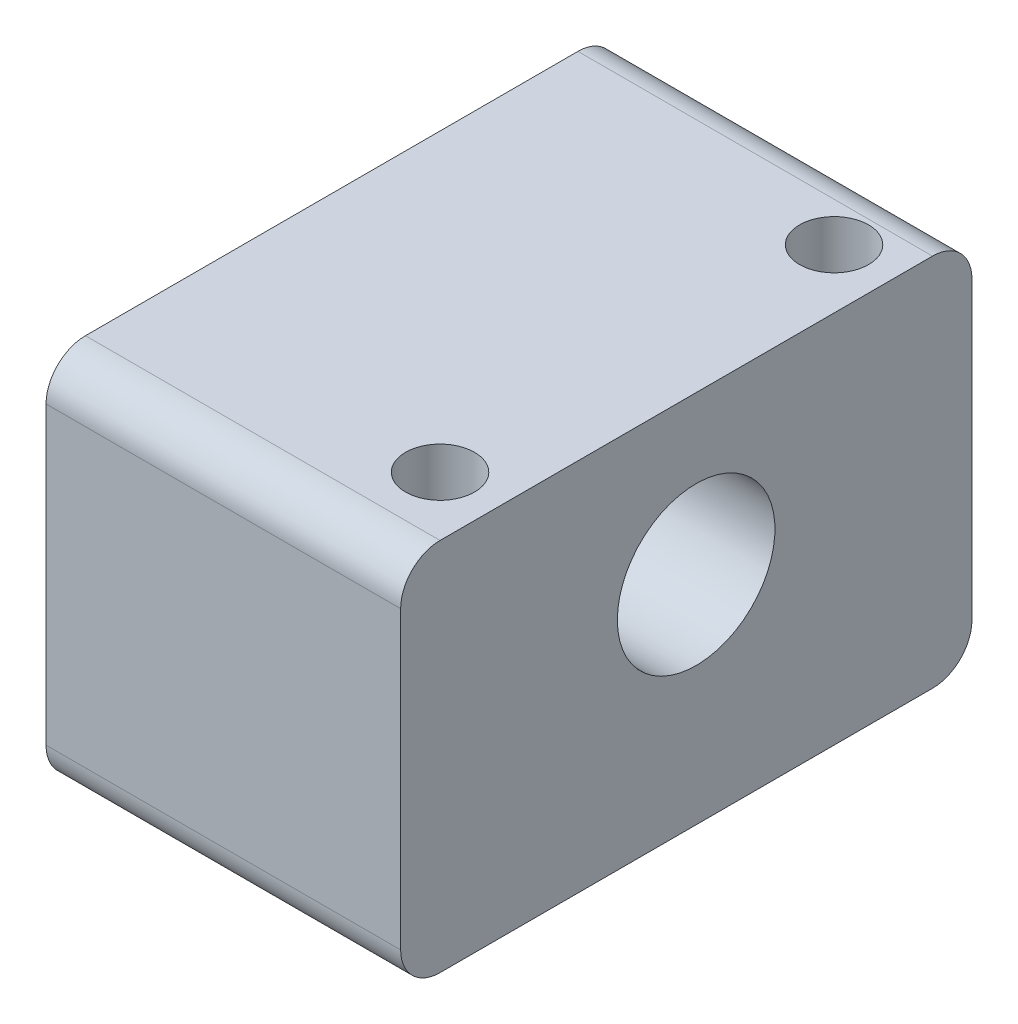
SolidWorks part; units mm, degrees
material "ABS"
ref_plane "前视基准面" through (0, 0, 0) normal (0, 0, 1) x (1, 0, 0)
ref_plane "上视基准面" through (0, 0, 0) normal (0, 1, 0) x (1, 0, 0)
ref_plane "右视基准面" through (0, 0, 0) normal (1, 0, 0) x (0, 0, -1)
other "Configuration Table"
sketch "草图1" plane through (0, 0, 0) normal (0, 1, 0) x (1, 0, 0)
  line L0 (6, 15) -> (6, 35) construction
  line L1 (-9, 39) -> (9, 39)
  line L2 (-9, 39) -> (-9, 10)
  line L3 (-9, 10) -> (9, 10)
  line L4 (9, 39) -> (9, 10)
  line L5 (-9, 39) -> (9, 10) construction
  line L6 (-9, 10) -> (9, 39) construction
  circle A0 centre (6, 15) radius 1.75
  circle A1 centre (6, 35) radius 1.75
  point P0 (0, 24.5)
  dimension "D5" = 3.5
  dimension "D1" = 18
  dimension "D2" = 29
  dimension "D3" = 10
  dimension "D4" = 3
  dimension "D6" = 15
  dimension "D7" = 20
extrude "凸台-拉伸1" add sketch "草图1" along normal blind 19
sketch "草图2" plane through (-9, 0, 0) normal (-1, 0, 0) x (0, 0, 1)
  line L0 (-25, 11) -> (-5, 11) construction
  line L1 (-39, 19) -> (-10, 19) construction
  circle A0 centre (-25, 11) radius 4
  circle A1 centre (-5, 11) radius 4
  point P4 (-15, 11)
  dimension "D3" = 8
  dimension "D1" = 20
  dimension "D2" = 5
  dimension "D4" = 8
extrude "切除-拉伸1" cut sketch "草图2" against normal blind 20
fillet "圆角1" radius 2 4 edges at (0, 0, -10) (0, 19, -10) (0, 0, -39) (0, 19, -39)
